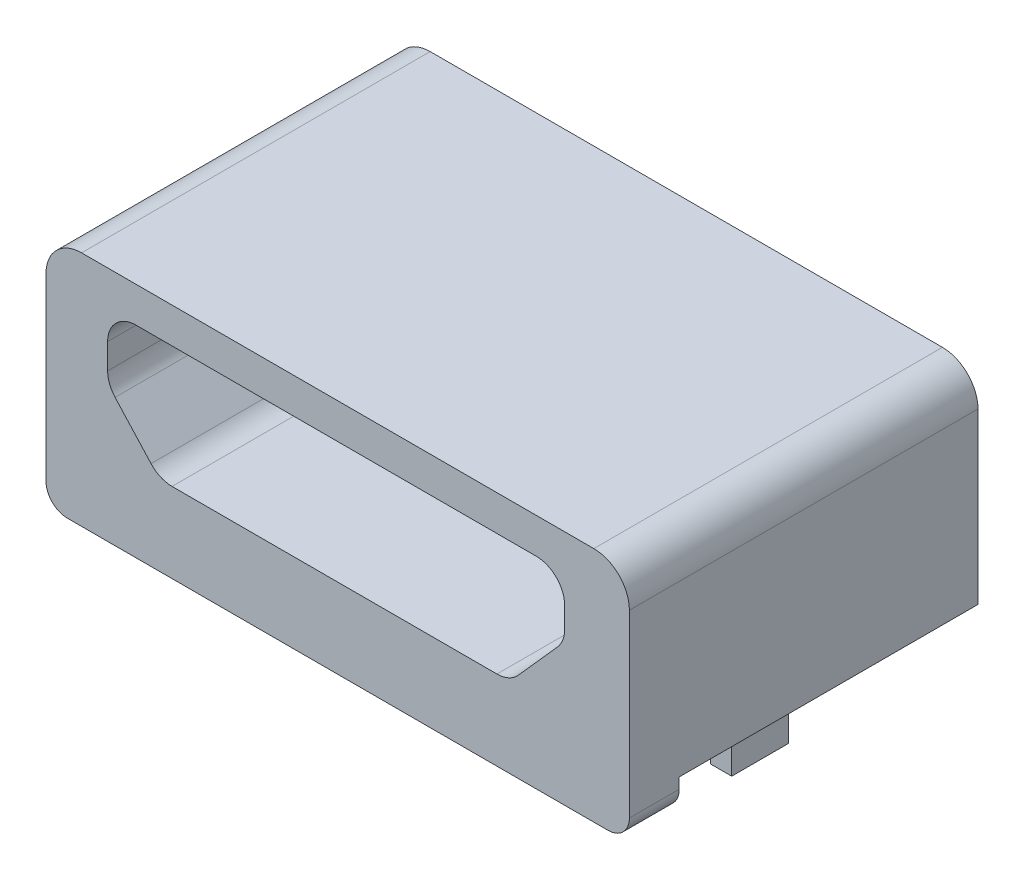
SolidWorks part; units mm, degrees
ref_plane "Front" through (0, 0, 0) normal (0, 0, 1) x (1, 0, 0)
ref_plane "Top" through (0, 0, 0) normal (0, 1, 0) x (1, 0, 0)
ref_plane "Right" through (0, 0, 0) normal (1, 0, 0) x (0, 0, -1)
sketch "Sketch1" plane through (0, 0, 0) normal (0, 0, 1) x (1, 0, 0)
  line L1 (0, 0) -> (8.2, 0)
  line L2 (0, 0) -> (0, 2.88)
  line L3 (0, 2.88) -> (8.2, 2.88)
  line L4 (8.2, 0) -> (8.2, 2.88)
  dimension "D1" = 2.88
  dimension "D2" = 8.2
extrude "Boss-Extrude1" add sketch "Sketch1" along normal blind 4.2
sketch "Sketch2" plane through (0, 0, 4.2) normal (0, 0, 1) x (1, 0, 0)
  line L0 (8.2, 0) -> (8.2, 2.88) construction
  line L1 (0, 2.88) -> (8.2, 2.88)
  line L2 (0, 2.88) -> (0, -0.45)
  line L3 (0, -0.45) -> (8.2, -0.45)
  line L4 (8.2, 2.88) -> (8.2, -0.45)
  line L5 (0, 0) -> (8.2, 0) construction
  dimension "D1" = 0.45
extrude "Boss-Extrude2" add sketch "Sketch2" along normal blind 0.7
fillet "Fillet1" radius 0.5 2 edges at (8.2, 2.88, 2.45) (0, 2.88, 2.45)
fillet "Fillet2" radius 0.3 2 edges at (8.2, -0.45, 4.55) (0, -0.45, 4.55)
sketch "Sketch3" plane through (0, 0, 4.9) normal (0, 0, 1) x (1, 0, 0)
  line L0 (1.2661, 2.3827) -> (6.8905, 2.3827)
  line L1 (7.2905, 1.9827) -> (7.2905, 1.6928)
  line L2 (7.1893, 1.4269) -> (6.6372, 0.8065)
  line L3 (6.3384, 0.6724) -> (1.7718, 0.6724)
  line L4 (1.4764, 0.8027) -> (0.9707, 1.3565)
  line L5 (0.8661, 1.6262) -> (0.8661, 1.9827)
  arc A0 (6.3384, 0.6724) -> (6.6372, 0.8065) centre (6.3384, 1.0724) ccw
  arc A1 (7.1893, 1.4269) -> (7.2905, 1.6928) centre (6.8905, 1.6928) ccw
  arc A2 (7.2905, 1.9827) -> (6.8905, 2.3827) centre (6.8905, 1.9827) ccw
  arc A3 (1.7718, 0.6724) -> (1.4764, 0.8027) centre (1.7718, 1.0724) cw
  arc A4 (0.9707, 1.3565) -> (0.8661, 1.6262) centre (1.2661, 1.6262) cw
  arc A5 (1.2661, 2.3827) -> (0.8661, 1.9827) centre (1.2661, 1.9827) ccw
  dimension "D1" = 0.4
extrude "Cut-Extrude1" cut sketch "Sketch3" against normal blind 3
sketch "Sketch4" plane through (0, 0, 0) normal (0, -1, 0) x (1, 0, 0)
  line L0 (0, 4.2) -> (0, 0) construction
  line L1 (0.34, 3.122) -> (0.64, 3.122)
  line L2 (0.34, 3.122) -> (0.34, 2.322)
  line L3 (0.34, 2.322) -> (0.64, 2.322)
  line L4 (0.64, 3.122) -> (0.64, 2.322)
  line L5 (7.86, 2.322) -> (7.56, 2.322)
  line L6 (7.86, 2.322) -> (7.86, 3.122)
  line L7 (7.86, 3.122) -> (7.56, 3.122)
  line L8 (7.56, 2.322) -> (7.56, 3.122)
  line L10 (0.3, 4.9) -> (7.9, 4.9) construction
  dimension "D1" = 0.3
  dimension "D2" = 0.3
  dimension "D3" = 0.8
  dimension "D4" = 7.22
  dimension "D5" = 0.34
  dimension "D6" = 1.778
extrude "Boss-Extrude3" add sketch "Sketch4" along normal blind 0.7
